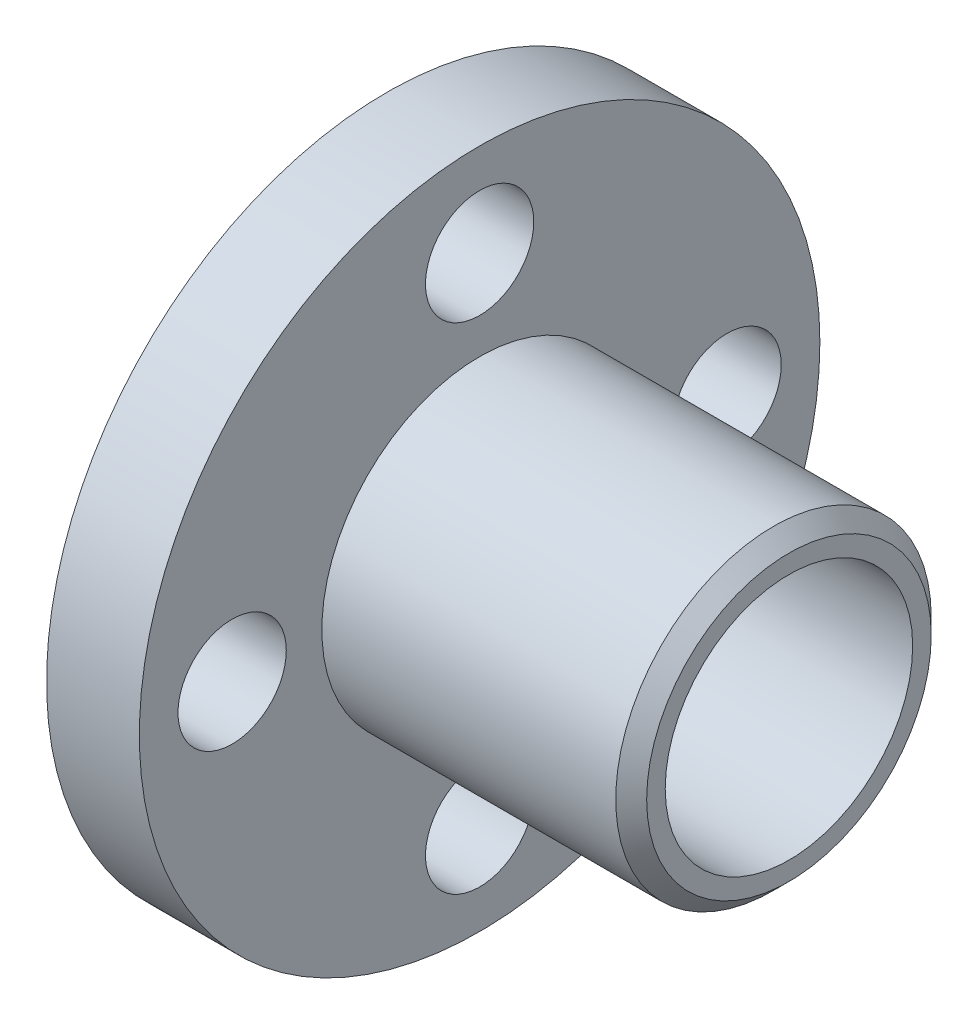
SolidWorks part; units mm, degrees
ref_plane "Alzado" through (0, 0, 0) normal (0, 0, 1) x (1, 0, 0)
ref_plane "Planta" through (0, 0, 0) normal (0, 1, 0) x (1, 0, 0)
ref_plane "Vista lateral" through (0, 0, 0) normal (1, 0, 0) x (0, 0, -1)
sketch "Croquis1" plane through (0, 0, 0) normal (1, 0, 0) x (0, 0, -1)
  line L0 (0, 11) -> (0, -11) construction
  line L1 (-11, 0) -> (11, 0) construction
  circle A0 centre (0, 0) radius 11
  circle A1 centre (0, 8) radius 1.75
  circle A2 centre (8, 0) radius 1.75
  circle A3 centre (0, -8) radius 1.75
  circle A4 centre (-8, 0) radius 1.75
  point P18 (0, 0)
  dimension "D1" = 22
  dimension "D3" = 3.5
  dimension "D2" = 8
  dimension "D4" = 4
extrude "Saliente-Extruir1" add sketch "Croquis1" along normal blind 3
sketch "Croquis2" plane through (3, 0, 0) normal (1, 0, 0) x (0, 0, -1)
  circle A0 centre (0, 0) radius 5.1
  dimension "D1" = 10.2
extrude "Saliente-Extruir2" add sketch "Croquis2" along normal blind 10
chamfer "Chaflán1" distance 0.5 angle 45 1 edges at (13, 0, -5.1)
sketch "Croquis3" plane through (0, 0, 0) normal (-1, 0, 0) x (0, 0, 1)
  circle A0 centre (0, 0) radius 5.1
  dimension "D1" = 10.2
extrude "Saliente-Extruir3" add sketch "Croquis3" along normal blind 1.5
sketch "Croquis4" plane through (13, 0, 0) normal (1, 0, 0) x (0, 0, -1)
  circle A0 centre (0, 0) radius 4
  dimension "D1" = 8
extrude "Cortar-Extruir1" cut sketch "Croquis4" against normal through all
